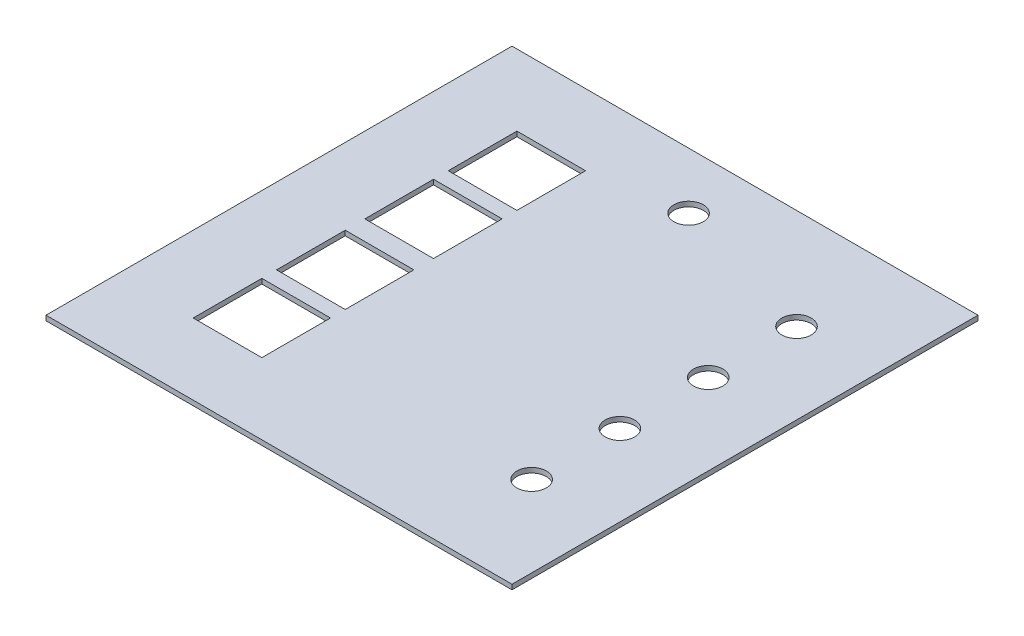
SolidWorks part; units mm, degrees
ref_plane "Front Plane" through (0, 0, 0) normal (0, 0, 1) x (1, 0, 0)
ref_plane "Top Plane" through (0, 0, 0) normal (0, 1, 0) x (1, 0, 0)
ref_plane "Right Plane" through (0, 0, 0) normal (1, 0, 0) x (0, 0, -1)
sketch "Sketch1" plane through (0, 0, 0) normal (0, 1, 0) x (1, 0, 0)
  line L1 (0, 0) -> (95, 0)
  line L2 (0, 0) -> (0, 95)
  line L3 (0, 95) -> (95, 95)
  line L4 (95, 0) -> (95, 95)
  dimension "D1" = 95
extrude "Boss-Extrude1" add sketch "Sketch1" along normal blind 1
sketch "Sketch2" plane through (0, 1, 0) normal (0, 1, 0) x (1, 0, 0)
  line L0 (0, 47.5) -> (95, 47.5) construction
  line L1 (29.5, 49.5) -> (15.5, 49.5)
  line L2 (29.5, 49.5) -> (29.5, 63.5)
  line L3 (29.5, 63.5) -> (15.5, 63.5)
  line L4 (15.5, 49.5) -> (15.5, 63.5)
  line L5 (15.5, 80.5) -> (29.5, 80.5)
  line L6 (15.5, 80.5) -> (15.5, 66.5)
  line L7 (15.5, 66.5) -> (29.5, 66.5)
  line L8 (29.5, 80.5) -> (29.5, 66.5)
  line L9 (0, 95) -> (0, 0) construction
  line L10 (95, 0) -> (95, 95) construction
  line L11 (15.5, 14.5) -> (29.5, 14.5)
  line L12 (29.5, 14.5) -> (29.5, 28.5)
  line L13 (15.5, 28.5) -> (29.5, 28.5)
  line L14 (15.5, 14.5) -> (15.5, 28.5)
  line L15 (15.5, 45.5) -> (15.5, 31.5)
  line L16 (29.5, 31.5) -> (15.5, 31.5)
  line L17 (29.5, 45.5) -> (29.5, 31.5)
  line L18 (29.5, 45.5) -> (15.5, 45.5)
  circle A0 centre (47.5, 83.5) radius 3
  circle A1 centre (78.5, 74.5) radius 3
  circle A2 centre (78.5, 56.5) radius 3
  circle A3 centre (78.5, 38.5) radius 3
  circle A4 centre (78.5, 20.5) radius 3
  point P14 (22.5, 63.5)
  point P18 (47.5, 47.5)
  point P22 (77.1, 56.5)
  dimension "D6" = 6
  dimension "D1" = 2
  dimension "D2" = 16
  dimension "D3" = 3
  dimension "D4" = 14
  dimension "D5" = 18
  dimension "D7" = 36
  dimension "D8" = 27
  dimension "D9" = 31
  dimension "D10" = 9
extrude "Cut-Extrude1" cut sketch "Sketch2" against normal up to surface (1 mm away) up to face at (47.5, 0, -47.5)
